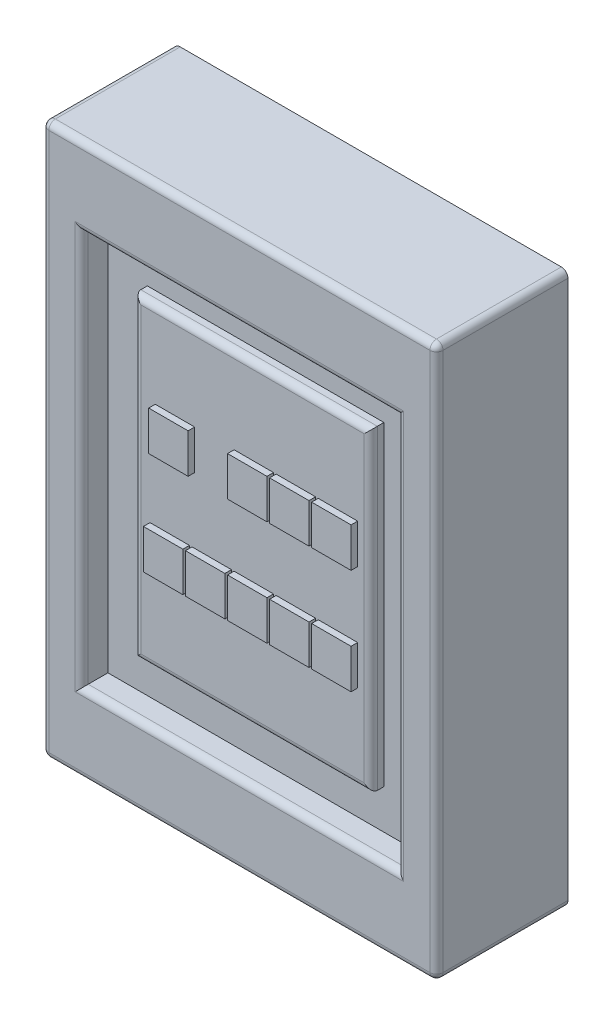
SolidWorks part; units mm, degrees
ref_plane "Front Plane" through (0, 0, 0) normal (0, 0, 1) x (1, 0, 0)
ref_plane "Top Plane" through (0, 0, 0) normal (0, 1, 0) x (1, 0, 0)
ref_plane "Right Plane" through (0, 0, 0) normal (1, 0, 0) x (0, 0, -1)
sketch "Sketch1" plane through (0, 0, 0) normal (0, 0, 1) x (1, 0, 0)
  line L1 (0, 0) -> (300, 0)
  line L2 (0, 0) -> (0, 420)
  line L3 (0, 420) -> (300, 420)
  line L4 (300, 0) -> (300, 420)
  dimension "D1" = 300
  dimension "D2" = 420
extrude "Boss-Extrude1" add sketch "Sketch1" along normal blind 100 contours L3 L4 L1 L2
sketch "Sketch2" plane through (0, 0, 100) normal (0, 0, 1) x (1, 0, 0)
  line L0 (0, 420) -> (300, 420) construction
  line L1 (30, 60) -> (270, 60)
  line L2 (30, 60) -> (30, 360)
  line L3 (30, 360) -> (270, 360)
  line L4 (270, 60) -> (270, 360)
  line L5 (300, 0) -> (300, 420) construction
  line L6 (0, 0) -> (300, 0) construction
  line L7 (0, 0) -> (0, 420) construction
  dimension "D1" = 60
  dimension "D2" = 30
  dimension "D3" = 60
  dimension "D4" = 30
extrude "Cut-Extrude1" cut sketch "Sketch2" against normal blind 20
sketch "Sketch3" plane through (0, 0, 80) normal (0, 0, 1) x (1, 0, 0)
  line L0 (60, 330) -> (60, 90)
  line L1 (60, 90) -> (240, 90)
  line L2 (240, 90) -> (240, 330)
  line L3 (240, 330) -> (60, 330)
  point P8 (0, 0)
  point P9 (0, 0)
extrude "Boss-Extrude2" add sketch "Sketch3" along normal blind 10
sketch "Sketch4" plane through (0, 0, 90) normal (0, 0, 1) x (1, 0, 0)
  line L0 (240, 330) -> (60, 330) construction
  line L1 (76, 265) -> (106, 265)
  line L2 (76, 265) -> (76, 235)
  line L3 (76, 235) -> (106, 235)
  line L4 (106, 265) -> (106, 235)
  line L5 (136, 265) -> (166, 265)
  line L6 (136, 265) -> (136, 235)
  line L7 (136, 235) -> (166, 235)
  line L8 (166, 265) -> (166, 235)
  line L9 (168, 265) -> (198, 265)
  line L10 (168, 265) -> (168, 235)
  line L11 (168, 235) -> (198, 235)
  line L12 (198, 265) -> (198, 235)
  line L13 (200, 265) -> (230, 265)
  line L14 (200, 265) -> (200, 235)
  line L15 (200, 235) -> (230, 235)
  line L16 (230, 265) -> (230, 235)
  line L17 (72, 185) -> (102, 185)
  line L18 (72, 185) -> (72, 155)
  line L19 (72, 155) -> (102, 155)
  line L20 (102, 185) -> (102, 155)
  line L21 (104, 185) -> (134, 185)
  line L22 (104, 185) -> (104, 155)
  line L23 (104, 155) -> (134, 155)
  line L24 (134, 185) -> (134, 155)
  line L25 (136, 185) -> (166, 185)
  line L26 (136, 185) -> (136, 155)
  line L27 (136, 155) -> (166, 155)
  line L28 (166, 185) -> (166, 155)
  line L29 (168, 185) -> (198, 185)
  line L30 (168, 185) -> (168, 155)
  line L31 (168, 155) -> (198, 155)
  line L32 (198, 185) -> (198, 155)
  line L33 (200, 185) -> (230, 185)
  line L34 (200, 185) -> (200, 155)
  line L35 (200, 155) -> (230, 155)
  line L36 (230, 185) -> (230, 155)
  line L37 (240, 90) -> (240, 330) construction
  line L38 (240, 90) -> (240, 330) construction
  dimension "D1" = 30
  dimension "D2" = 30
  dimension "D3" = 30
  dimension "D4" = 30
  dimension "D5" = 30
  dimension "D6" = 30
  dimension "D7" = 30
  dimension "D8" = 30
  dimension "D9" = 30
  dimension "D10" = 30
  dimension "D11" = 30
  dimension "D12" = 30
  dimension "D13" = 30
  dimension "D14" = 30
  dimension "D15" = 30
  dimension "D16" = 30
  dimension "D17" = 30
  dimension "D18" = 30
  dimension "D19" = 2
  dimension "D20" = 2
  dimension "D21" = 2
  dimension "D22" = 2
  dimension "D23" = 10
  dimension "D24" = 10
  dimension "D25" = 2
  dimension "D26" = 2
  dimension "D27" = 30
  dimension "D28" = 50
  dimension "D29" = 65
extrude "Boss-Extrude3" add sketch "Sketch4" along normal blind 5
fillet "Fillet1" radius 5 12 edges at (270, 210, 100) (150, 360, 100) (30, 210, 100) (150, 60, 100) (150, 420, 100) (300, 210, 100) (150, 0, 100) (0, 210, 100) (0, 0, 50) (300, 0, 50) (0, 420, 50) (300, 420, 50)
fillet "Fillet2" radius 5 4 edges at (150, 330, 90) (60, 210, 90) (240, 210, 90) (150, 90, 90)
